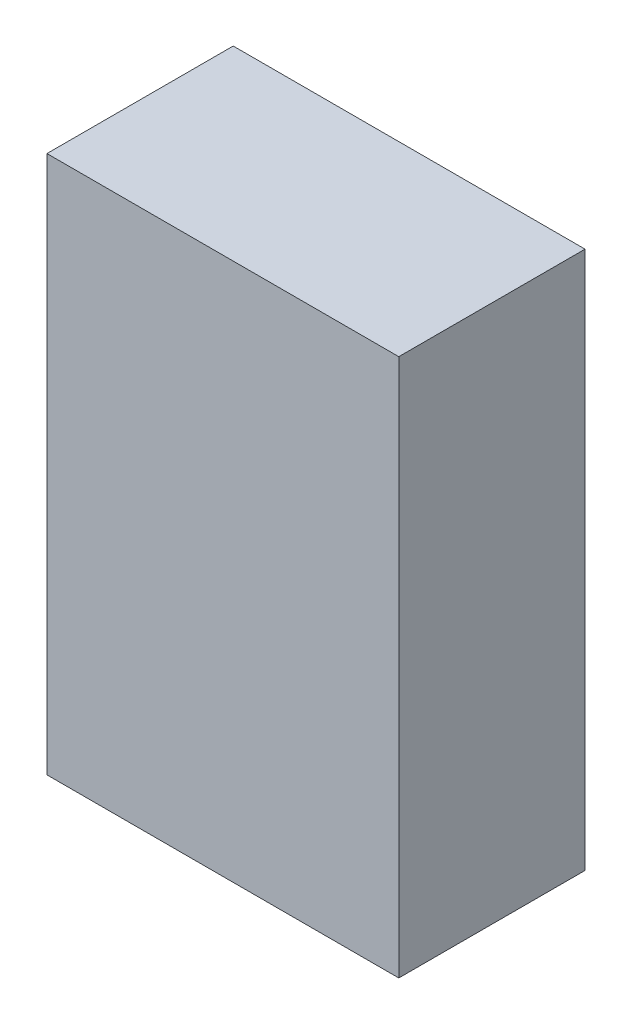
SolidWorks part; units mm, degrees
ref_plane "前视基准面" through (0, 0, 0) normal (0, 0, 1) x (1, 0, 0)
ref_plane "上视基准面" through (0, 0, 0) normal (0, 1, 0) x (1, 0, 0)
ref_plane "右视基准面" through (0, 0, 0) normal (1, 0, 0) x (0, 0, -1)
other "Configuration Table"
sketch "草图1" plane through (0, 0, 0) normal (0, 0, 1) x (1, 0, 0)
  line L1 (-17, -26) -> (17, -26)
  line L2 (-17, -26) -> (-17, 26)
  line L3 (-17, 26) -> (17, 26)
  line L4 (17, -26) -> (17, 26)
extrude "凸台-拉伸1" add sketch "草图1" against normal blind 18
